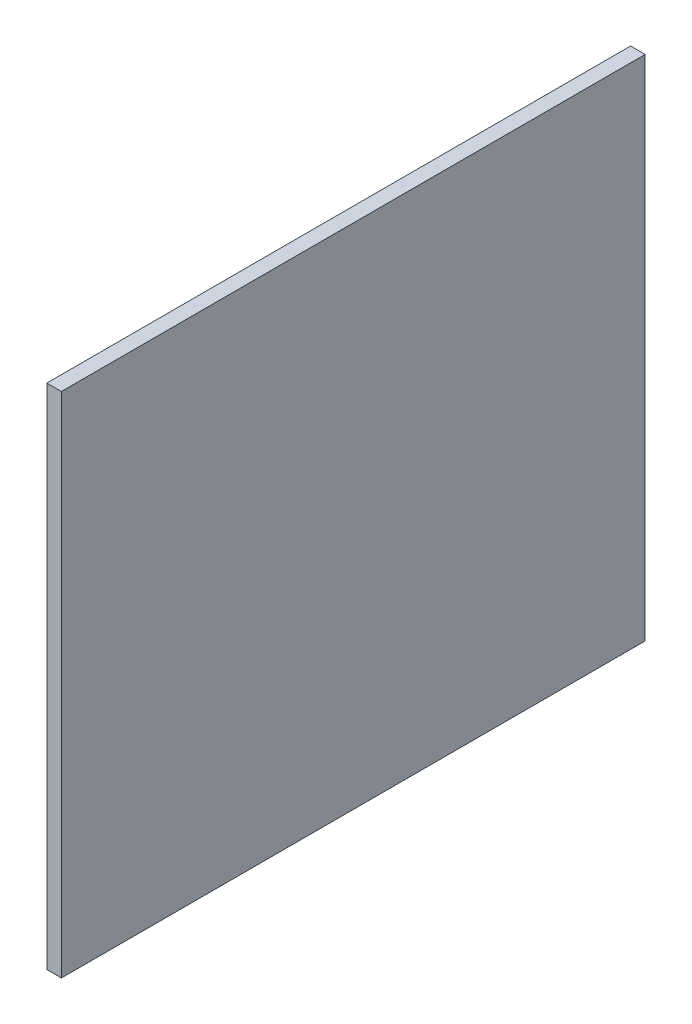
SolidWorks part; units mm, degrees
ref_plane "Front Plane" through (0, 0, 0) normal (0, 0, 1) x (1, 0, 0)
ref_plane "Top Plane" through (0, 0, 0) normal (0, 1, 0) x (1, 0, 0)
ref_plane "Right Plane" through (0, 0, 0) normal (1, 0, 0) x (0, 0, -1)
sketch "Sketch1" plane through (0, 0, 0) normal (1, 0, 0) x (0, 0, -1)
  line L1 (0, 0) -> (1000, 0)
  line L2 (0, 0) -> (0, 870)
  line L3 (0, 870) -> (1000, 870)
  line L4 (1000, 0) -> (1000, 870)
  dimension "D1" = 870
  dimension "D2" = 1000
extrude "Boss-Extrude1" add sketch "Sketch1" along normal blind 25
